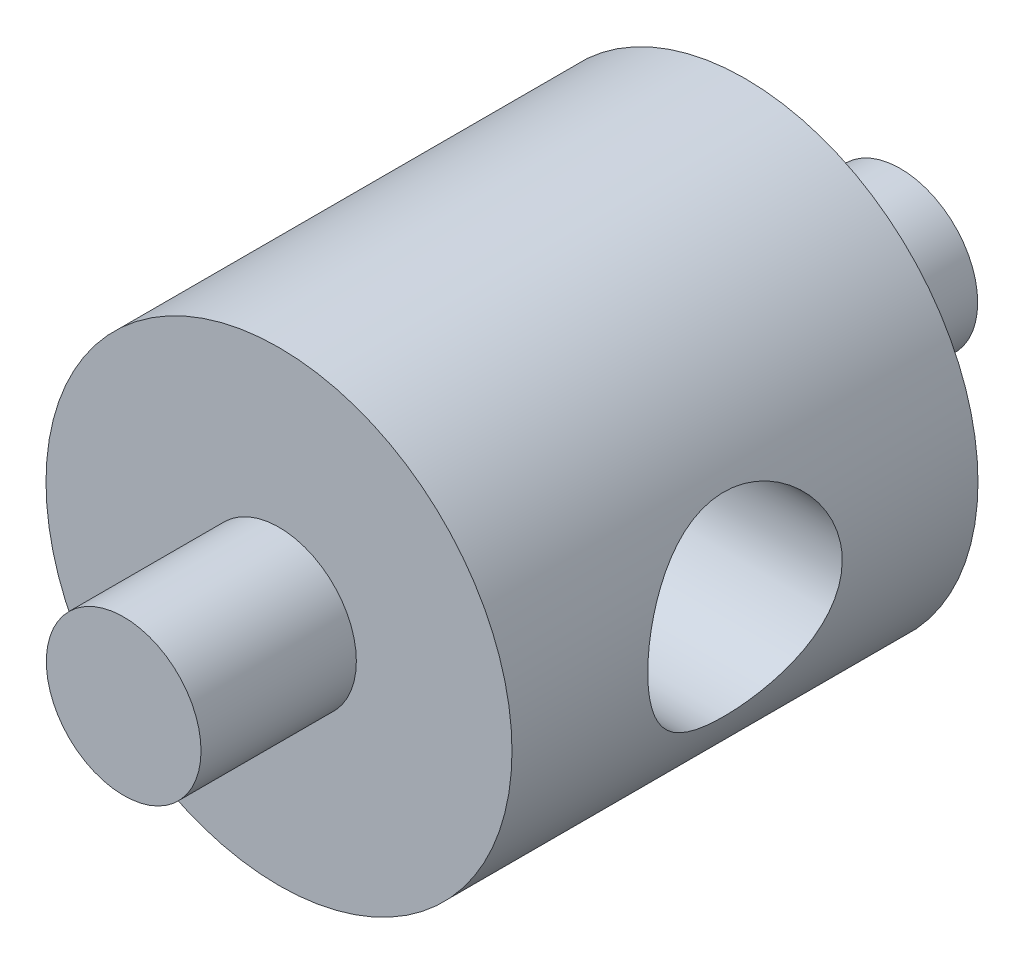
SolidWorks part; units mm, degrees
ref_plane "Front Plane" through (0, 0, 0) normal (0, 0, 1) x (1, 0, 0)
ref_plane "Top Plane" through (0, 0, 0) normal (0, 1, 0) x (1, 0, 0)
ref_plane "Right Plane" through (0, 0, 0) normal (1, 0, 0) x (0, 0, -1)
sketch "Sketch1" plane through (0, 0, 0) normal (0, 0, 1) x (1, 0, 0)
  circle A0 centre (0, 0) radius 9.525
  dimension "D1" = 19.05
extrude "Boss-Extrude1" add sketch "Sketch1" along normal blind 19.05
sketch "Sketch2" plane through (0, 0, 19.05) normal (0, 0, 1) x (1, 0, 0)
  circle A0 centre (0, 0) radius 3.1623
  dimension "D1" = 6.3246
extrude "Boss-Extrude2" add sketch "Sketch2" along normal blind 6.35 and the other way blind 25.4
sketch "Sketch3" plane through (0, 0, 0) normal (1, 0, 0) x (0, 0, -1)
  circle A0 centre (-9.525, 0) radius 3.9751
  dimension "D1" = 7.9502
extrude "Cut-Extrude1" cut sketch "Sketch3" against normal through all both and the other way through all
